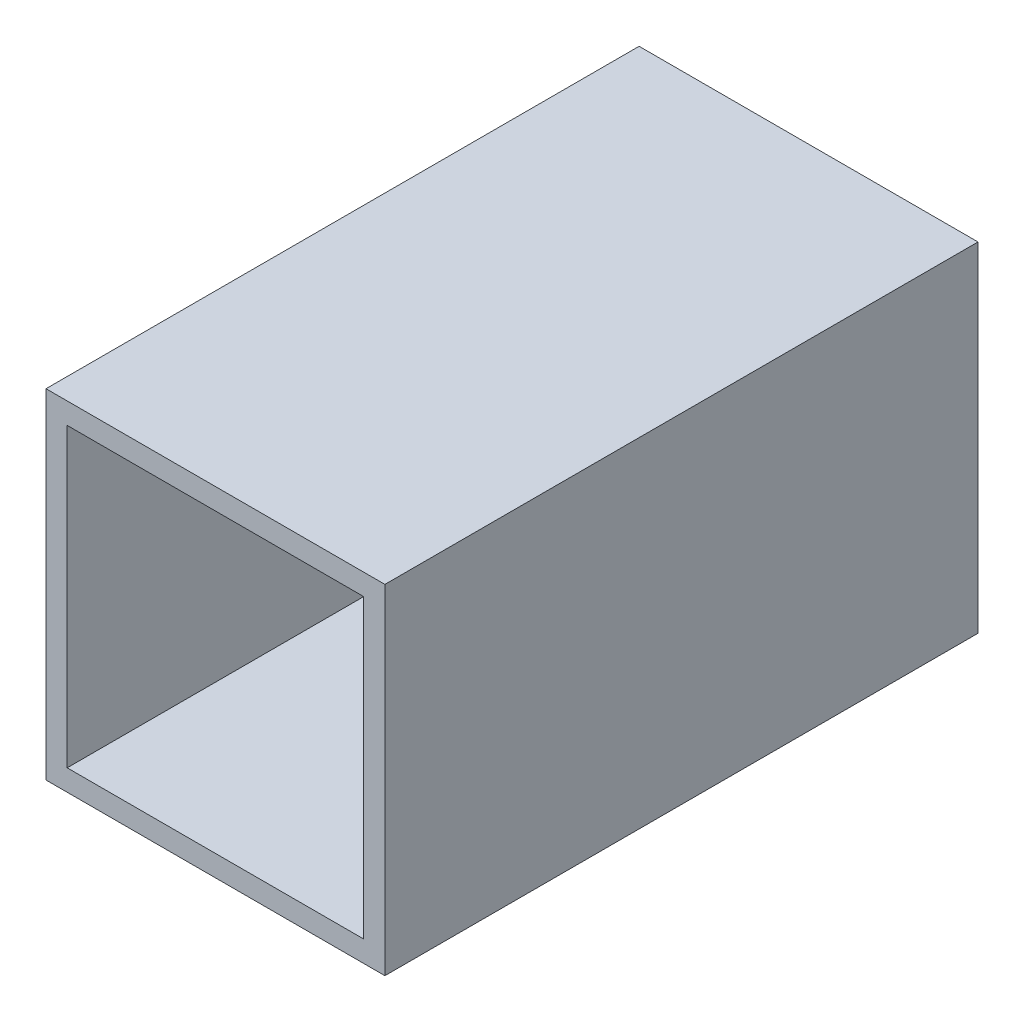
SolidWorks part; units mm, degrees
ref_plane "Front Plane" through (0, 0, 0) normal (0, 0, 1) x (1, 0, 0)
ref_plane "Top Plane" through (0, 0, 0) normal (0, 1, 0) x (1, 0, 0)
ref_plane "Right Plane" through (0, 0, 0) normal (1, 0, 0) x (0, 0, -1)
sketch "Sketch1" plane through (0, 0, 0) normal (0, 0, 1) x (1, 0, 0)
  line L1 (-12.7, 12.7) -> (12.7, 12.7)
  line L2 (-12.7, 12.7) -> (-12.7, -12.7)
  line L3 (-12.7, -12.7) -> (12.7, -12.7)
  line L4 (12.7, 12.7) -> (12.7, -12.7)
  line L5 (-12.7, 12.7) -> (12.7, -12.7) construction
  line L6 (-12.7, -12.7) -> (12.7, 12.7) construction
  line L7 (11.1125, -11.1125) -> (-11.1125, -11.1125)
  line L8 (11.1125, -11.1125) -> (11.1125, 11.1125)
  line L9 (11.1125, 11.1125) -> (-11.1125, 11.1125)
  line L10 (-11.1125, -11.1125) -> (-11.1125, 11.1125)
  line L11 (11.1125, -11.1125) -> (-11.1125, 11.1125) construction
  line L12 (11.1125, 11.1125) -> (-11.1125, -11.1125) construction
  point P0 (0, 0)
  point P6 (0, 0)
  dimension "D1" = 25.4
  dimension "D2" = 1.5875
extrude "Boss-Extrude1" add sketch "Sketch1" along normal blind 44.45
other "1in Square tube<1>"
